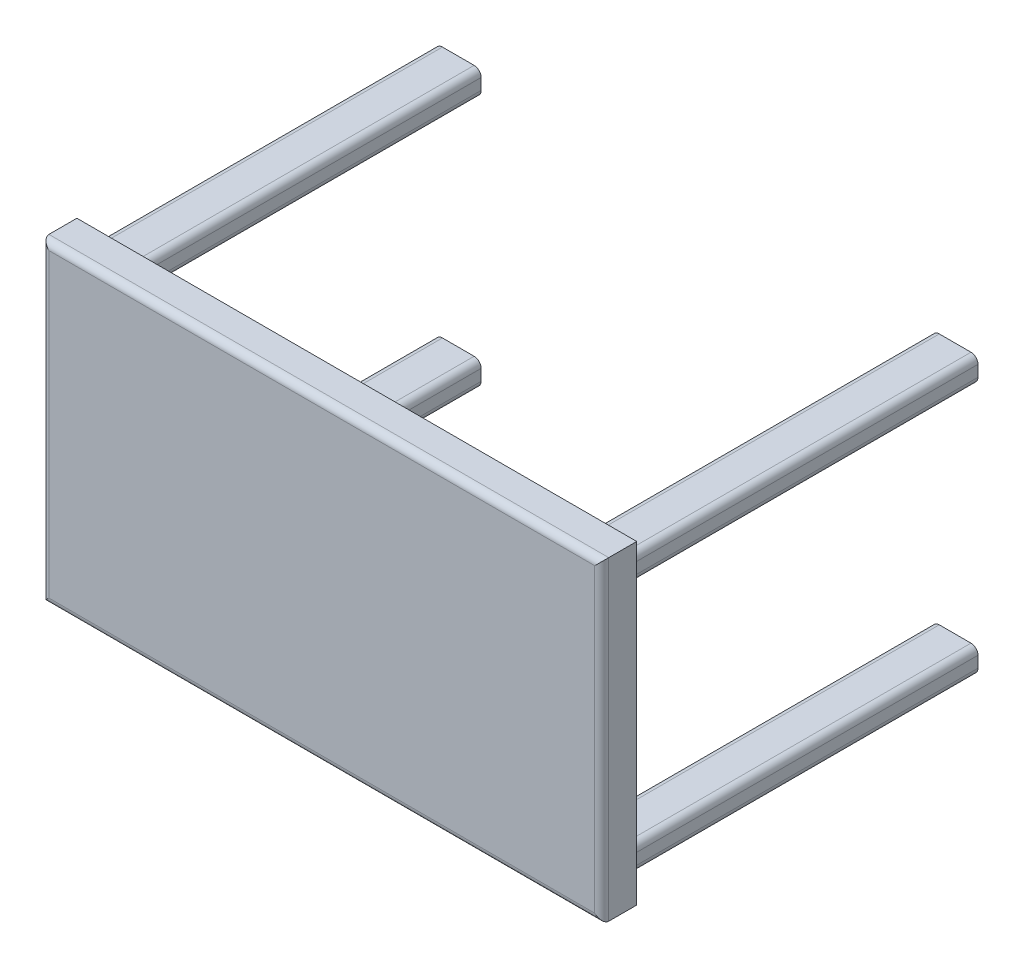
SolidWorks part; units mm, degrees
ref_plane "Plan de face" through (0, 0, 0) normal (0, 0, 1) x (1, 0, 0)
ref_plane "Plan de dessus" through (0, 0, 0) normal (0, 1, 0) x (1, 0, 0)
ref_plane "Plan de droite" through (0, 0, 0) normal (1, 0, 0) x (0, 0, -1)
sketch "Sketch1" plane through (0, 0, 0) normal (0, 0, 1) x (1, 0, 0)
  line L1 (-400, -225) -> (400, -225)
  line L2 (-400, -225) -> (-400, 225)
  line L3 (-400, 225) -> (400, 225)
  line L4 (400, -225) -> (400, 225)
  line L5 (-400, -225) -> (400, 225) construction
  line L6 (-400, 225) -> (400, -225) construction
  point P0 (0, 0)
  dimension "D1" = 450
  dimension "D2" = 800
extrude "Table" add sketch "Sketch1" along normal blind 50
sketch "Sketch2" plane through (0, 0, 0) normal (0, 0, -1) x (-1, 0, 0)
  line L0 (400, -225) -> (-400, -225) construction
  line L1 (387.6462, -162.0029) -> (322.3538, -162.0029)
  line L2 (387.6462, -162.0029) -> (387.6462, -197.9971)
  line L3 (387.6462, -197.9971) -> (322.3538, -197.9971)
  line L4 (322.3538, -162.0029) -> (322.3538, -197.9971)
  line L5 (387.6462, -162.0029) -> (322.3538, -197.9971) construction
  line L6 (387.6462, -197.9971) -> (322.3538, -162.0029) construction
  line L7 (400, 225) -> (400, -225) construction
  point P0 (355, -180)
  dimension "D1" = 45
  dimension "D2" = 45
extrude "pied" add sketch "Sketch2" along normal blind 500
pattern_linear "LPattern3" count 2 spacing 710 along (1, 0, 0) count 2 spacing 360 along (0, 1, 0) of "pied"
fillet "Fillet1" radius 10 4 edges at (400, 0, 50) (0, -225, 50) (-400, 0, 50) (0, 225, 50)
fillet "Fillet2" radius 10 4 edges at (-387.6462, -162.0029, -250) (-387.6462, -197.9971, -250) (-322.3538, -162.0029, -250) (-322.3538, -197.9971, -250)
fillet "Fillet3" radius 10 4 edges at (322.3538, -162.0029, -250) (387.6462, -162.0029, -250) (387.6462, -197.9971, -250) (322.3538, -197.9971, -250)
fillet "Fillet4" radius 10 4 edges at (322.3538, 162.0029, -250) (387.6462, 162.0029, -250) (322.3538, 197.9971, -250) (387.6462, 197.9971, -250)
fillet "Fillet5" radius 10 4 edges at (-322.3538, 162.0029, -250) (-387.6462, 162.0029, -250) (-322.3538, 197.9971, -250) (-387.6462, 197.9971, -250)
